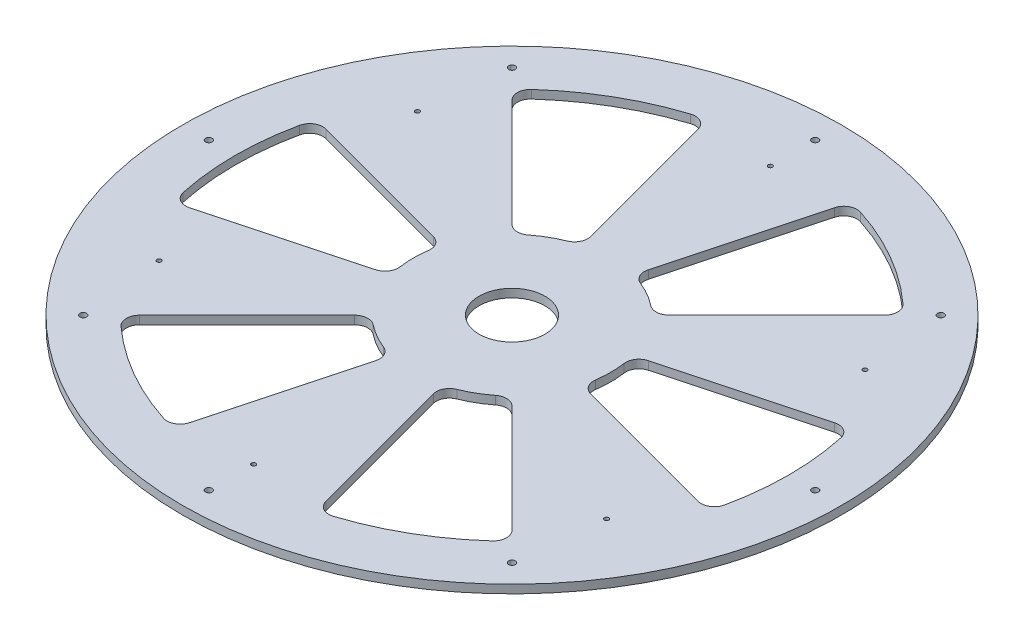
SolidWorks part; units mm, degrees
material "6061 Alloy"
ref_plane "Front Plane" through (0, 0, 0) normal (0, 0, 1) x (1, 0, 0)
ref_plane "Top Plane" through (0, 0, 0) normal (0, 1, 0) x (1, 0, 0)
ref_plane "Right Plane" through (0, 0, 0) normal (1, 0, 0) x (0, 0, -1)
sketch "Sketch1" plane through (0, 0, 0) normal (0, 1, 0) x (1, 0, 0)
  line L0 (0, 0) -> (-105, 181.8653) construction
  line L1 (0, 0) -> (-54.352, 202.8444) construction
  line L2 (-51.6991, 192.9435) -> (-21.8468, 81.5335)
  line L3 (-141.2445, 141.2445) -> (-59.6867, 59.6867)
  line L4 (141.2445, 141.2445) -> (59.6867, 59.6867)
  line L5 (51.6991, 192.9435) -> (21.8468, 81.5335)
  line L6 (192.9435, -51.6991) -> (81.5335, -21.8468)
  line L7 (192.9435, 51.6991) -> (81.5335, 21.8468)
  line L8 (51.6991, -192.9435) -> (21.8468, -81.5335)
  line L9 (141.2445, -141.2445) -> (59.6867, -59.6867)
  line L10 (-141.2445, -141.2445) -> (-59.6867, -59.6867)
  line L11 (-51.6991, -192.9435) -> (-21.8468, -81.5335)
  line L12 (-192.9435, 51.6991) -> (-81.5335, 21.8468)
  line L13 (-192.9435, -51.6991) -> (-81.5335, -21.8468)
  circle A0 centre (0, 0) radius 196 construction
  circle A1 centre (0, 196) radius 2 construction
  circle A2 centre (169.741, 98) radius 2 construction
  circle A3 centre (169.741, -98) radius 2 construction
  circle A4 centre (0, -196) radius 2 construction
  circle A5 centre (-169.741, -98) radius 2 construction
  circle A6 centre (-169.741, 98) radius 2 construction
  circle A7 centre (0, 0) radius 250
  circle A8 centre (-98, 169.741) radius 5 construction
  circle A9 centre (98, 169.741) radius 5 construction
  circle A10 centre (196, 0) radius 5 construction
  circle A11 centre (98, -169.741) radius 5 construction
  circle A12 centre (-98, -169.741) radius 5 construction
  circle A13 centre (-196, 0) radius 5 construction
  circle A14 centre (0, 0) radius 210 construction
  circle A15 centre (0, 0) radius 75 construction
  arc A16 (-140.8821, 155.7313) -> (-64.4262, 199.8731) centre (0, 0) cw
  arc A17 (-27.7995, 69.6576) -> (-46.4255, 58.9039) centre (0, 0) ccw
  arc A18 (-21.8468, 81.5335) -> (-27.7995, 69.6576) centre (-31.5061, 78.9453) cw
  arc A19 (-46.4255, 58.9039) -> (-59.6867, 59.6867) centre (-52.6156, 66.7577) cw
  arc A20 (-141.2445, 141.2445) -> (-140.8821, 155.7313) centre (-134.1734, 148.3155) cw
  arc A21 (-51.6991, 192.9435) -> (-64.4262, 199.8731) centre (-61.3583, 190.3553) ccw
  arc A22 (59.6867, 59.6867) -> (46.4255, 58.9039) centre (52.6156, 66.7577) cw
  arc A23 (27.7995, 69.6576) -> (21.8468, 81.5335) centre (31.5061, 78.9453) cw
  arc A24 (46.4255, 58.9039) -> (27.7995, 69.6576) centre (0, 0) ccw
  arc A25 (64.4262, 199.8731) -> (140.8821, 155.7313) centre (0, 0) cw
  arc A26 (141.2445, 141.2445) -> (140.8821, 155.7313) centre (134.1734, 148.3155) ccw
  arc A27 (51.6991, 192.9435) -> (64.4262, 199.8731) centre (61.3583, 190.3553) cw
  arc A28 (81.5335, -21.8468) -> (74.225, -10.7538) centre (84.1217, -12.1876) cw
  arc A29 (74.225, 10.7538) -> (81.5335, 21.8468) centre (84.1217, 12.1876) cw
  arc A30 (74.225, -10.7538) -> (74.225, 10.7538) centre (0, 0) ccw
  arc A31 (205.3083, 44.1418) -> (205.3083, -44.1418) centre (0, 0) cw
  arc A32 (192.9435, -51.6991) -> (205.3083, -44.1418) centre (195.5317, -42.0398) ccw
  arc A33 (192.9435, 51.6991) -> (205.3083, 44.1418) centre (195.5317, 42.0398) cw
  arc A34 (21.8468, -81.5335) -> (27.7995, -69.6576) centre (31.5061, -78.9453) cw
  arc A35 (46.4255, -58.9039) -> (59.6867, -59.6867) centre (52.6156, -66.7577) cw
  arc A36 (27.7995, -69.6576) -> (46.4255, -58.9039) centre (0, 0) ccw
  arc A37 (140.8821, -155.7313) -> (64.4262, -199.8731) centre (0, 0) cw
  arc A38 (51.6991, -192.9435) -> (64.4262, -199.8731) centre (61.3583, -190.3553) ccw
  arc A39 (141.2445, -141.2445) -> (140.8821, -155.7313) centre (134.1734, -148.3155) cw
  arc A40 (-59.6867, -59.6867) -> (-46.4255, -58.9039) centre (-52.6156, -66.7577) cw
  arc A41 (-27.7995, -69.6576) -> (-21.8468, -81.5335) centre (-31.5061, -78.9453) cw
  arc A42 (-46.4255, -58.9039) -> (-27.7995, -69.6576) centre (0, 0) ccw
  arc A43 (-64.4262, -199.8731) -> (-140.8821, -155.7313) centre (0, 0) cw
  arc A44 (-141.2445, -141.2445) -> (-140.8821, -155.7313) centre (-134.1734, -148.3155) ccw
  arc A45 (-51.6991, -192.9435) -> (-64.4262, -199.8731) centre (-61.3583, -190.3553) cw
  arc A46 (-81.5335, 21.8468) -> (-74.225, 10.7538) centre (-84.1217, 12.1876) cw
  arc A47 (-74.225, -10.7538) -> (-81.5335, -21.8468) centre (-84.1217, -12.1876) cw
  arc A48 (-74.225, 10.7538) -> (-74.225, -10.7538) centre (0, 0) ccw
  arc A49 (-205.3083, -44.1418) -> (-205.3083, 44.1418) centre (0, 0) cw
  arc A50 (-192.9435, 51.6991) -> (-205.3083, 44.1418) centre (-195.5317, 42.0398) ccw
  arc A51 (-192.9435, -51.6991) -> (-205.3083, -44.1418) centre (-195.5317, -42.0398) cw
  circle A52 centre (0, 0) radius 25
  circle A53 centre (0, 0) radius 230 construction
  circle A54 centre (0, 230) radius 3 construction
  circle A55 centre (162.6346, 162.6346) radius 3 construction
  circle A56 centre (230, 0) radius 3 construction
  circle A57 centre (162.6346, -162.6346) radius 3 construction
  circle A58 centre (0, -230) radius 3 construction
  circle A59 centre (-162.6346, -162.6346) radius 3 construction
  circle A60 centre (-230, 0) radius 3 construction
  circle A61 centre (-162.6346, 162.6346) radius 3 construction
  point P18 (0, 0)
  point P31 (0, 0)
  point P43 (-19.4114, 72.4444)
  point P46 (-53.033, 53.033)
  point P49 (-148.4924, 148.4924)
  point P113 (0, 0)
  point P132 (0, 0)
  dimension "D1" = 392
  dimension "D2" = 4
  dimension "D4" = 500
  dimension "D5" = 10
  dimension "D7" = 420
  dimension "D8" = 150
  dimension "D10" = 10
  dimension "D12" = 50
  dimension "D13" = 460
  dimension "D14" = 6
  dimension "D9" = 15
  dimension "D3" = 6
  dimension "D6" = 6
  dimension "D11" = 6
  dimension "D15" = 8
extrude "Boss-Extrude1" add sketch "Sketch1" against normal blind 6.35 contours A7
hole_wizard "Tap Drill for M4x0.7 Tap1" positions "3DSketch1" profile "Sketch2" hole size "M4x0.7" standard "ANSI Metric" end condition through all
sketch3d "3DSketch1"
  point P0 (0, 0, -196)
  point P2 (-169.741, 0, -98)
  point P4 (169.741, 0, -98)
  point P6 (169.741, 0, 98)
  point P8 (-169.741, 0, 98)
  point P10 (0, 0, 196)
sketch "Sketch2" plane through (0, 0, -196) normal (1, 0, 0) x (0, 0, 1)
  line L0 (0, 0) -> (0, 6.35)
  line L1 (0, 6.35) -> (1.65, 6.35)
  line L2 (1.65, 6.35) -> (1.65, 0)
  line L5 (1.65, 0) -> (0, 0)
  line L11 (0, -6.35) -> (0, 107.95) construction
  dimension "Thru Hole Dia." = 3.3
  dimension "Thru Hole Depth" = 6.35
hole_wizard "Tap Drill for M6x1.0 Tap1" positions "3DSketch2" profile "Sketch3" hole size "M6x1.0" standard "ANSI Metric" end condition through all
sketch3d "3DSketch2"
  point P0 (0, 0, -230)
  point P2 (162.6346, 0, -162.6346)
  point P4 (230, 0, 0)
  point P6 (-230, 0, 0)
  point P8 (-162.6346, 0, -162.6346)
  point P10 (0, 0, 230)
  point P12 (-162.6346, 0, 162.6346)
  point P14 (162.6346, 0, 162.6346)
sketch "Sketch3" plane through (0, 0, -230) normal (1, 0, 0) x (0, 0, 1)
  line L0 (0, 0) -> (0, 6.35)
  line L1 (0, 6.35) -> (2.5, 6.35)
  line L2 (2.5, 6.35) -> (2.5, 0)
  line L5 (2.5, 0) -> (0, 0)
  line L11 (0, -6.35) -> (0, 107.95) construction
  dimension "Thru Hole Dia." = 5
  dimension "Thru Hole Depth" = 6.35
